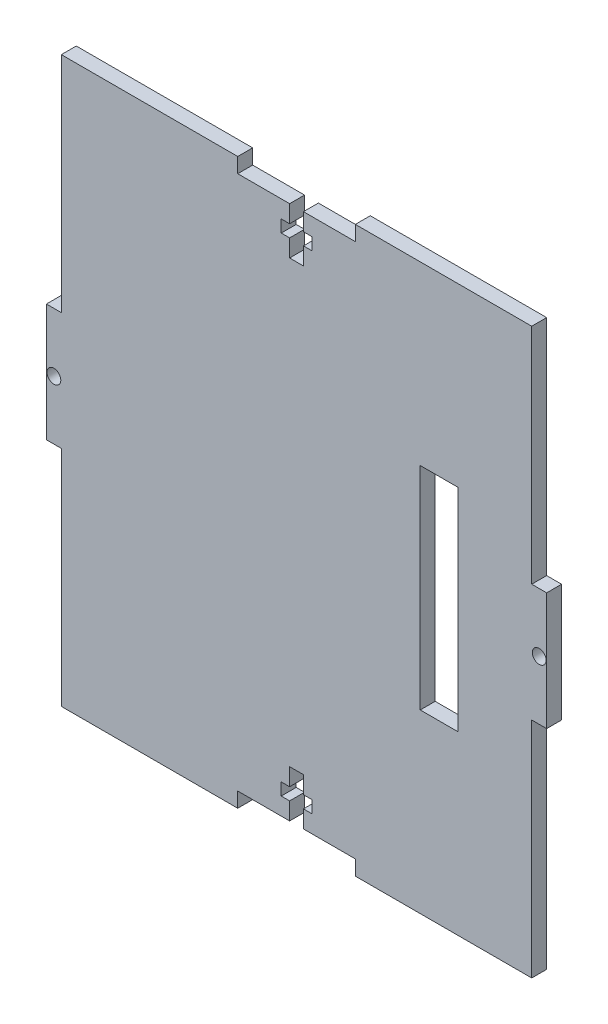
SolidWorks part; units mm, degrees
ref_plane "Front Plane" through (0, 0, 0) normal (0, 0, 1) x (1, 0, 0)
ref_plane "Top Plane" through (0, 0, 0) normal (0, 1, 0) x (1, 0, 0)
ref_plane "Right Plane" through (0, 0, 0) normal (1, 0, 0) x (0, 0, -1)
sketch "Sketch1" plane through (0, 0, 0) normal (0, 0, 1) x (1, 0, 0)
  line L0 (0, 60) -> (0, -60) construction
  line L1 (-50, 60) -> (50, 60)
  line L2 (-50, 60) -> (-50, -60)
  line L3 (-50, -60) -> (50, -60)
  line L4 (50, 60) -> (50, -60)
  line L5 (-50, 60) -> (50, -60) construction
  line L6 (-50, -60) -> (50, 60) construction
  line L7 (-50, 0) -> (50, 0) construction
  line L8 (-3.25, -50.525) -> (3.25, -50.525)
  line L9 (12.5, 60) -> (-12.5, 60)
  line L10 (12.5, 60) -> (12.5, 56.825)
  line L11 (12.5, 56.825) -> (-12.5, 56.825)
  line L12 (-12.5, 60) -> (-12.5, 56.825)
  line L13 (12.5, 60) -> (-12.5, 56.825) construction
  line L14 (12.5, 56.825) -> (-12.5, 60) construction
  line L15 (-1.47, 56.825) -> (1.47, 56.825)
  line L16 (-1.47, 56.825) -> (-1.47, 46.825)
  line L17 (-1.47, 46.825) -> (1.47, 46.825)
  line L18 (1.47, 56.825) -> (1.47, 46.825)
  line L19 (-1.47, 56.825) -> (1.47, 46.825) construction
  line L20 (-1.47, 46.825) -> (1.47, 56.825) construction
  line L21 (-3.25, 53.125) -> (3.25, 53.125)
  line L22 (-3.25, 53.125) -> (-3.25, 50.525)
  line L23 (-3.25, 50.525) -> (3.25, 50.525)
  line L24 (3.25, 53.125) -> (3.25, 50.525)
  line L25 (-3.25, 53.125) -> (3.25, 50.525) construction
  line L26 (-3.25, 50.525) -> (3.25, 53.125) construction
  line L27 (3.25, -53.125) -> (3.25, -50.525)
  line L28 (-3.25, -53.125) -> (3.25, -53.125)
  line L29 (-3.25, -53.125) -> (-3.25, -50.525)
  line L30 (-1.47, -46.825) -> (1.47, -46.825)
  line L31 (1.47, -56.825) -> (1.47, -46.825)
  line L32 (-1.47, -56.825) -> (1.47, -56.825)
  line L33 (-1.47, -56.825) -> (-1.47, -46.825)
  line L34 (12.5, -56.825) -> (-12.5, -56.825)
  line L35 (-12.5, -60) -> (-12.5, -56.825)
  line L36 (12.5, -60) -> (-12.5, -60)
  line L37 (12.5, -60) -> (12.5, -56.825)
  line L38 (53.175, -12.5) -> (50, -12.5)
  line L39 (-53.175, 12.5) -> (-50, 12.5)
  line L40 (-53.175, 12.5) -> (-53.175, -12.5)
  line L41 (-53.175, -12.5) -> (-50, -12.5)
  line L42 (-50, 12.5) -> (-50, -12.5)
  line L43 (-53.175, 12.5) -> (-50, -12.5) construction
  line L44 (-53.175, -12.5) -> (-50, 12.5) construction
  line L45 (50, 12.5) -> (50, -12.5)
  line L46 (53.175, 12.5) -> (50, 12.5)
  line L47 (53.175, 12.5) -> (53.175, -12.5)
  circle A0 centre (-51.5875, 0) radius 1.47
  circle A1 centre (51.5875, 0) radius 1.47
  point P0 (0, 0)
  point P10 (0, 58.4125)
  point P15 (0, 51.825)
  point P20 (0, 51.825)
  point P37 (-51.5875, 0)
  dimension "D11" = 2.94
  dimension "D1" = 120
  dimension "D2" = 100
  dimension "D3" = 3.175
  dimension "D4" = 10
  dimension "D5" = 2.94
  dimension "D6" = 25
  dimension "D7" = 6.5
  dimension "D8" = 2.6
  dimension "D9" = 6.3
  dimension "D10" = 3.175
extrude "Boss-Extrude1" add sketch "Sketch1" along normal mid plane 3.175 contours L21 L24 L23 L18 L17 L16 L22 L11 L12 L1 L2 L3 L4 L10 | L40 L39 L42 L41 | A0 | L38 L45 L46 L47 | A1
sketch "Sketch3" plane through (0, 0, -1.5875) normal (0, 0, -1) x (-1, 0, 0)
  line L6 (-30.3, 22.5) -> (-30.3, -22.5) construction
  line L7 (-26.3, 22.5) -> (-34.3, 22.5)
  line L8 (-26.3, 22.5) -> (-26.3, -22.5)
  line L9 (-26.3, -22.5) -> (-34.3, -22.5)
  line L10 (-34.3, 22.5) -> (-34.3, -22.5)
  line L11 (-28.7125, -25) -> (-28.7125, 25) construction
  line L12 (-31.8875, 25) -> (-31.8875, -25) construction
  line L13 (0, 0) -> (-5.1205, 0) construction
  dimension "D1" = 8
  dimension "D2" = 45
extrude "Cut-Extrude1" cut sketch "Sketch3" against normal through all
